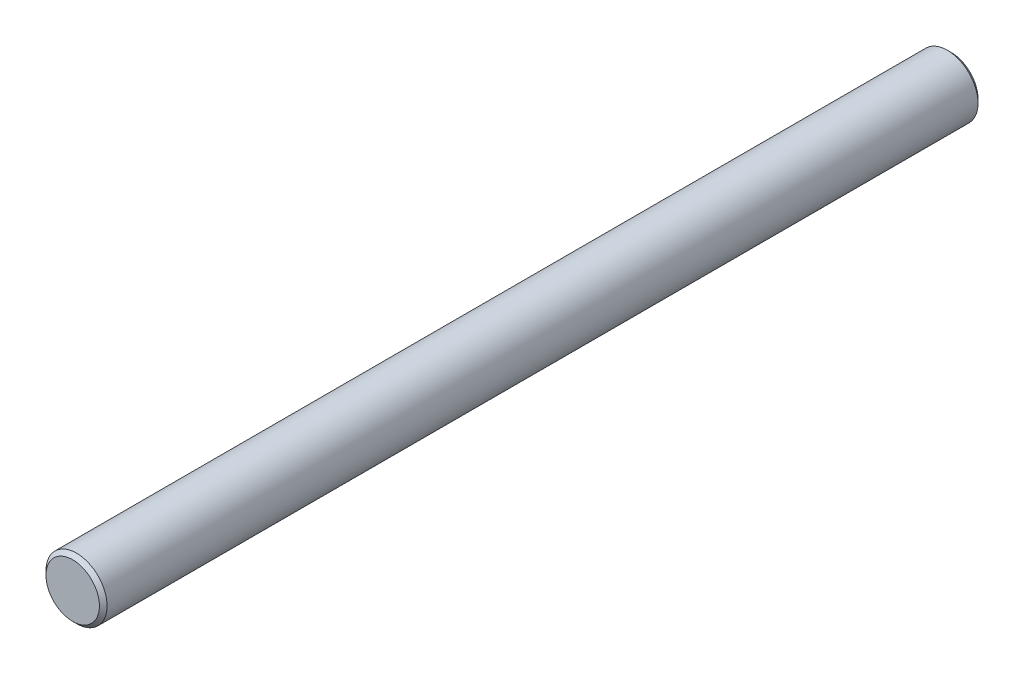
SolidWorks part; units mm, degrees
material "Stainless Steel (ferritic)"
ref_plane "Front Plane" through (0, 0, 0) normal (0, 0, 1) x (1, 0, 0)
ref_plane "Top Plane" through (0, 0, 0) normal (0, 1, 0) x (1, 0, 0)
ref_plane "Right Plane" through (0, 0, 0) normal (1, 0, 0) x (0, 0, -1)
sketch "Sketch1" plane through (0, 0, 0) normal (0, 0, 1) x (1, 0, 0)
  circle A0 centre (0, 0) radius 4
  dimension "D1" = 8
extrude "Boss-Extrude1" add sketch "Sketch1" along normal mid plane 115
chamfer "Chamfer1" distance 0.5 angle 45 2 edges at (4, 0, -57.5) (4, 0, 57.5)
